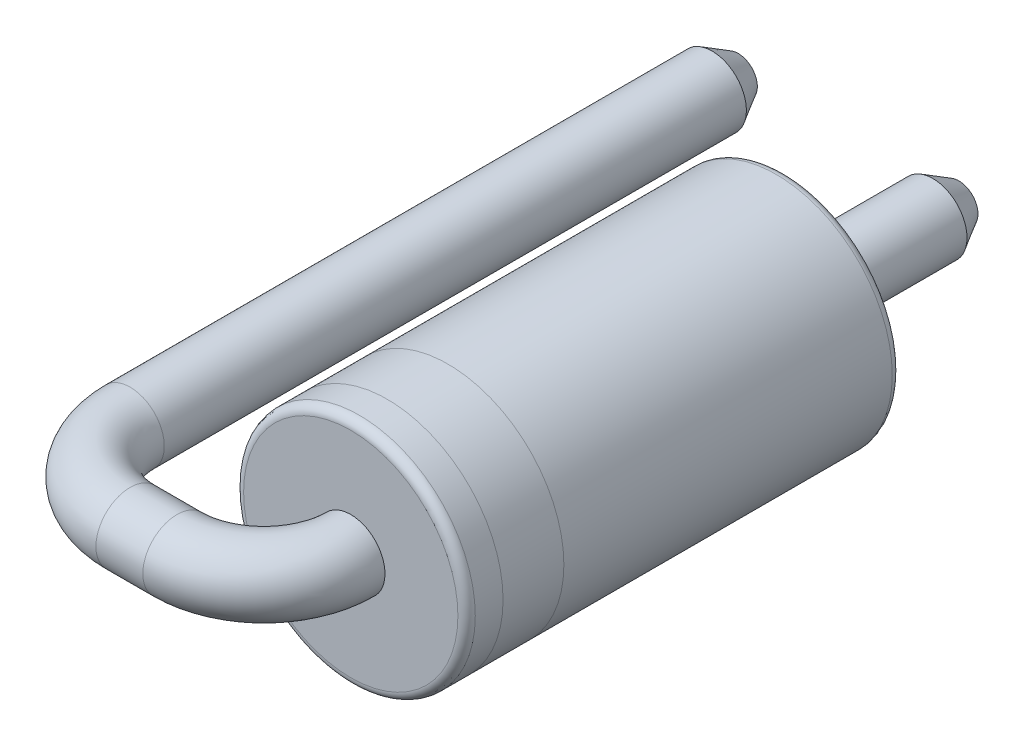
SolidWorks part; units mm, degrees
ref_plane "Front Plane" through (0, 0, 0) normal (0, 0, 1) x (1, 0, 0)
ref_plane "Top Plane" through (0, 0, 0) normal (0, 1, 0) x (1, 0, 0)
ref_plane "Right Plane" through (0, 0, 0) normal (1, 0, 0) x (0, 0, -1)
sketch "Sketch1" plane through (0, 0, 0) normal (0, 0, 1) x (1, 0, 0)
  line L0 (-83.7806, 0) -> (81.6596, 0) construction
  circle A0 centre (1.27, 0) radius 0.3937
  dimension "D1" = 0.7874
  dimension "D2" = 1.27
sketch "Sketch3" plane through (0, 0, 0) normal (0, 1, 0) x (1, 0, 0)
  line L0 (1.27, 0) -> (1.27, -7)
  line L1 (0.27, -8) -> (-0.27, -8)
  line L2 (-1.27, -7) -> (-1.27, 0)
  line L3 (-200083.7806, 0) -> (200081.6596, 0) construction
  arc A0 (-0.27, -8) -> (-1.27, -7) centre (-0.27, -7) cw
  arc A1 (1.27, -7) -> (0.27, -8) centre (0.27, -7) cw
  point P9 (-1.27, -8)
  point P12 (1.27, -8)
  dimension "D3" = 1
  dimension "D1" = 8
  dimension "D2" = 2.54
sweep "Sweep1" add profiles "Sketch1" path "Sketch3"
sketch3d "3DSketch4" plane through (0, 0, 0) normal (0, 0, 1) x (1, 0, 0)
  dimension "D1" = 2
sketch "Sketch4" plane through (0, 0, 2) normal (0, 0, 1) x (1, 0, 0)
  circle A0 centre (1.27, 0) radius 1.3335
  dimension "D1" = 2.667
chamfer "Chamfer1" distance 0.3 angle 30 2 edges at (1.6637, 0, 0) (-1.6637, 0, 0)
extrude "Extrude2" add sketch "Sketch4" along normal blind 5
sketch "Sketch5" plane through (0, 0, 0) normal (0, 1, 0) x (1, 0, 0)
  line L1 (3.1625, -5.8802) -> (-0.4751, -5.8802)
  line L2 (3.1625, -5.8802) -> (3.1625, -6.5802)
  line L3 (3.1625, -6.5802) -> (-0.4751, -6.5802)
  line L4 (-0.4751, -5.8802) -> (-0.4751, -6.5802)
  dimension "D1" = 0.7
split line "Split Line15"
fillet "Fillet2" radius 0.1 2 edges at (2.6035, 0, 2) (2.6035, 0, 7)
